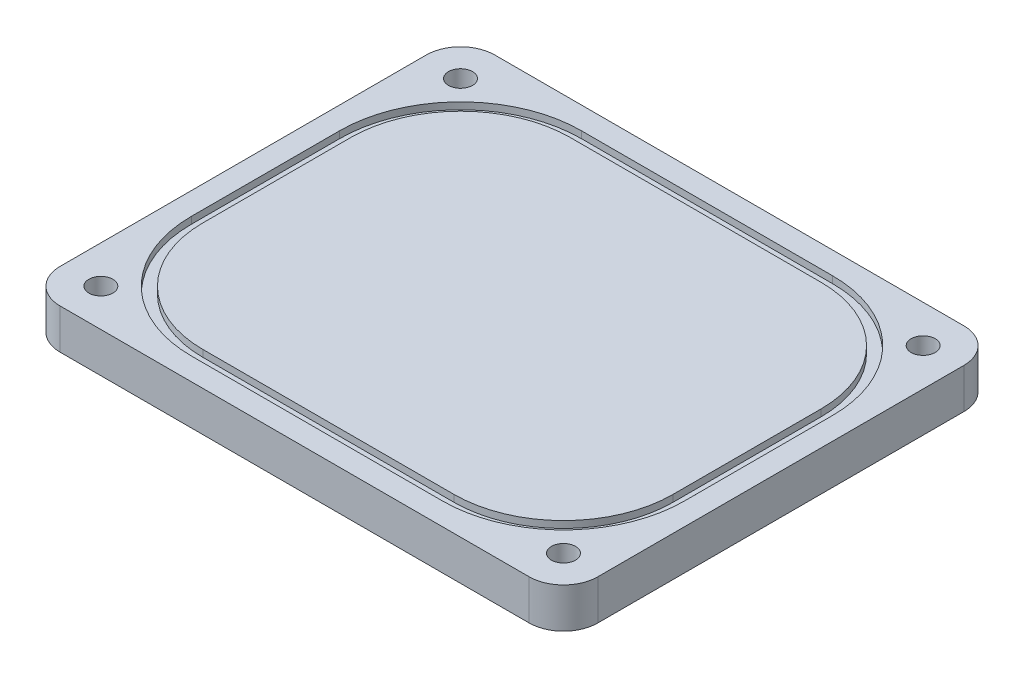
SolidWorks part; units mm, degrees
ref_plane "Front Plane" through (0, 0, 0) normal (0, 0, 1) x (1, 0, 0)
ref_plane "Top Plane" through (0, 0, 0) normal (0, 1, 0) x (1, 0, 0)
ref_plane "Right Plane" through (0, 0, 0) normal (1, 0, 0) x (0, 0, -1)
sketch "Sketch1" plane through (0, 0, 0) normal (0, 1, 0) x (1, 0, 0)
  line L1 (-47, -38) -> (47, -38)
  line L2 (-47, -38) -> (-47, 38)
  line L3 (-47, 38) -> (47, 38)
  line L4 (47, -38) -> (47, 38)
  line L5 (-47, -38) -> (47, 38) construction
  line L6 (-47, 38) -> (47, -38) construction
  point P0 (0, 0)
  dimension "D1" = 76
  dimension "D2" = 94
extrude "Boss-Extrude1" add sketch "Sketch1" along normal blind 7
fillet "Fillet1" radius 6 4 edges at (-47, 3.5, -38) (47, 3.5, -38) (47, 3.5, 38) (-47, 3.5, 38)
sketch "Sketch2" plane through (0, 7, 0) normal (0, 1, 0) x (1, 0, 0)
  line L0 (-47, 32) -> (-47, -32) construction
  line L1 (41, 38) -> (-41, 38) construction
  circle A0 centre (-40.44, 31.44) radius 2.1
  circle A1 centre (40.44, 31.44) radius 2.1
  circle A2 centre (40.44, -31.44) radius 2.1
  circle A3 centre (-40.44, -31.44) radius 2.1
  point P6 (0, 0)
  dimension "D2" = 4.2
  dimension "D1" = 6.56
  dimension "6.56" = 6.56
  dimension "D3" = 2
  dimension "D4" = 2
extrude "Cut-Extrude1" cut sketch "Sketch2" against normal through all both and the other way through all
sketch "Sketch3" plane through (0, 7, 0) normal (0, 1, 0) x (1, 0, 0)
  line L0 (-41.1, -12.96) -> (-41.1, 12.96)
  line L1 (-40.44, -31.44) -> (40.44, -31.44) construction
  line L2 (-40.44, -31.44) -> (-40.44, 31.44) construction
  line L3 (-40.44, 31.44) -> (40.44, 31.44) construction
  line L4 (40.44, -31.44) -> (40.44, 31.44) construction
  line L5 (-40.44, -31.44) -> (40.44, 31.44) construction
  line L6 (-40.44, 31.44) -> (40.44, -31.44) construction
  line L7 (21.96, 32.1) -> (-21.96, 32.1)
  line L8 (0, 32.1) -> (0, -31.44) construction
  line L9 (-41.1, 0) -> (40.44, 0) construction
  line L10 (-21.96, 34.1) -> (21.96, 34.1)
  line L11 (-43.1, -12.96) -> (-43.1, 12.96)
  line L12 (-21.96, -34.1) -> (21.96, -34.1)
  line L13 (21.96, -32.1) -> (-21.96, -32.1)
  line L14 (41.1, -12.96) -> (41.1, 12.96)
  line L15 (43.1, -12.96) -> (43.1, 12.96)
  arc A0 (-41.1, 12.96) -> (-21.96, 32.1) centre (-21.96, 12.96) cw
  arc A1 (-43.1, 12.96) -> (-21.96, 34.1) centre (-21.96, 12.96) cw
  arc A2 (-41.1, -12.96) -> (-21.96, -32.1) centre (-21.96, -12.96) ccw
  arc A3 (-43.1, -12.96) -> (-21.96, -34.1) centre (-21.96, -12.96) ccw
  arc A4 (43.1, 12.96) -> (21.96, 34.1) centre (21.96, 12.96) ccw
  arc A5 (41.1, 12.96) -> (21.96, 32.1) centre (21.96, 12.96) ccw
  arc A6 (41.1, -12.96) -> (21.96, -32.1) centre (21.96, -12.96) cw
  arc A7 (43.1, -12.96) -> (21.96, -34.1) centre (21.96, -12.96) cw
  point P0 (0, 0)
  point P10 (-41.1, 0)
  point P13 (0, 32.1)
  dimension "D1" = 41.1
  dimension "D2" = 25.92
  dimension "D3" = 32.1
  dimension "D4" = 43.92
  dimension "D5" = 2
extrude "Cut-Extrude2" cut sketch "Sketch3" against normal blind 1.2
sketch "Sketch4" plane through (0, 0, 0) normal (0, -1, 0) x (1, 0, 0)
  circle A1 centre (-40.44, 31.44) radius 4.2
  circle A2 centre (40.44, 31.44) radius 4.2
  circle A3 centre (40.44, -31.44) radius 4.2
  circle A4 centre (-40.44, -31.44) radius 4.2
  dimension "D1" = 8.4
  dimension "D2" = 8.4
  dimension "D3" = 8.4
  dimension "D4" = 8.4
extrude "Cut-Extrude3" cut sketch "Sketch4" against normal blind 2.75
sketch "Sketch5" plane through (0, 0, 0) normal (0, -1, 0) x (1, 0, 0)
  line L0 (-33.9764, 0) -> (33.9764, 0) construction
  text T0 "<b>MSGC</b>"
  point P4 (0, 0)
extrude "Cut-Extrude4" cut sketch "Sketch5" against normal blind 0.25
